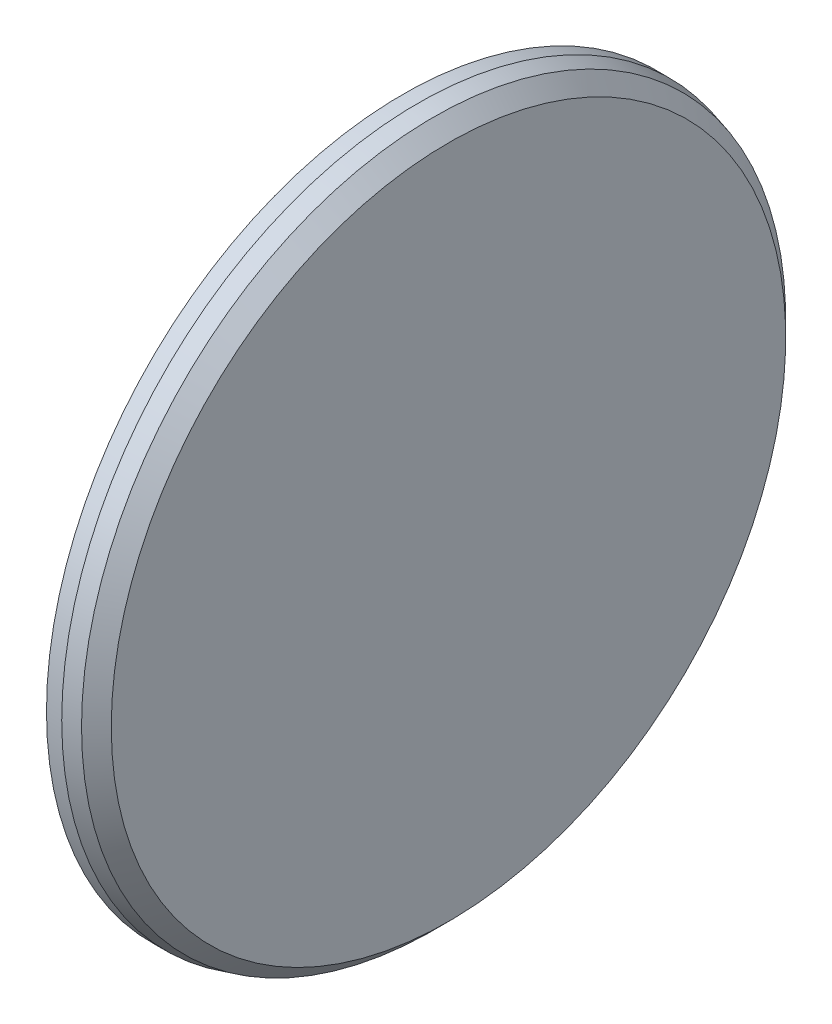
SolidWorks part; units mm, degrees
material "1060 Alloy"
ref_plane "Front Plane" through (0, 0, 0) normal (0, 0, 1) x (1, 0, 0)
ref_plane "Top Plane" through (0, 0, 0) normal (0, 1, 0) x (1, 0, 0)
ref_plane "Right Plane" through (0, 0, 0) normal (1, 0, 0) x (0, 0, -1)
sketch "Sketch1" plane through (0, 0, 0) normal (0, 1, 0) x (1, 0, 0)
  line L0 (0, 0) -> (60, 0)
  line L1 (60, 0) -> (60, 442.5)
  line L5 (0, 467.5) -> (0, 0)
  line L8 (20, 467.5) -> (0, 467.5)
  line L9 (60, 442.5) -> (40.4904, 462.0096)
  line L10 (40.4904, 462.0096) -> (20, 467.5)
  line L11 (20, 467.5) -> (43.6922, 467.5) construction
  line L12 (40.4904, 462.0096) -> (71.9516, 462.0096) construction
  dimension "D1" = 467.5
  dimension "D2" = 60
  dimension "D3" = 442.5
  dimension "D4" = 20
  dimension "D5" = 15
  dimension "D6" = 45
revolve "Revolve1" add sketch "Sketch1" angle 360 about L0
sketch "Sketch2" plane through (0, 0, 0) normal (-1, 0, 0) x (0, 0, 1)
  circle A0 centre (0, 0) radius 100
  dimension "D1" = 200
extrude "Boss-Extrude1" add sketch "Sketch2" along normal blind 20
sketch "Sketch3" plane through (0, 0, 0) normal (-1, 0, 0) x (0, 0, 1)
  circle A0 centre (0, 0) radius 422.5
  circle A1 centre (0, 0) radius 467.5 construction
  dimension "D1" = 45
extrude "Cut-Extrude1" cut sketch "Sketch3" against normal blind 30
equation "\"A\"= 60mm"
equation "\"B\"= 935.00mm"
